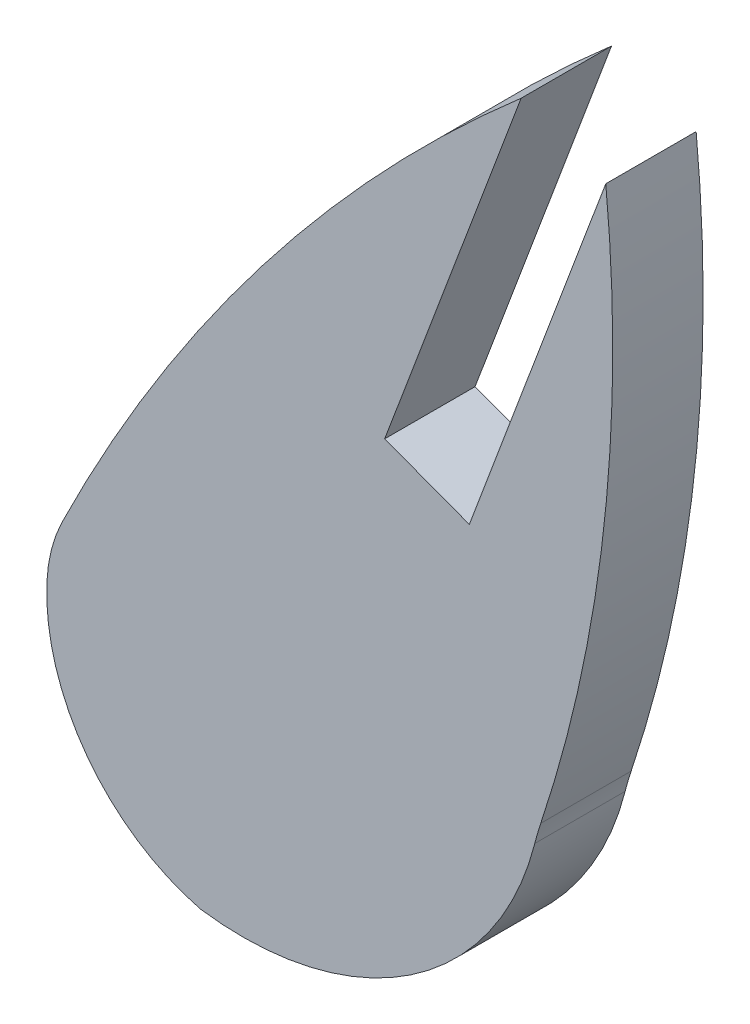
SolidWorks part; units mm, degrees
ref_plane "Front" through (0, 0, 0) normal (0, 0, 1) x (1, 0, 0)
ref_plane "Top" through (0, 0, 0) normal (0, 1, 0) x (1, 0, 0)
ref_plane "Right" through (0, 0, 0) normal (1, 0, 0) x (0, 0, -1)
sketch "Sketch1" plane through (0, 0, 0) normal (0, 0, 1) x (1, 0, 0)
  line L0 (-834.8343, -87.679) -> (-839.3645, -99.7367)
  line L1 (-839.3645, -99.7367) -> (-842.1728, -98.6816)
  line L2 (-842.1728, -98.6816) -> (-837.6427, -86.6239)
  arc A0 (-848.2815, -115.2586) -> (-837.1909, -107.8226) centre (-846.8822, -105.357) ccw
  arc A1 (-836.992, -107.1425) -> (-834.8343, -87.679) centre (-881.661, -92.3393) ccw
  arc A2 (-848.2815, -115.2586) -> (-853.3861, -108.4206) centre (-846.6302, -108.7016) cw
  arc A3 (-852.8802, -106.4281) -> (-837.6427, -86.6239) centre (-796.449, -134.0827) cw
  arc A4 (-853.3861, -108.4206) -> (-852.8802, -106.4281) centre (-848.3904, -108.6284) cw
  arc A5 (-836.992, -107.1425) -> (-837.1909, -107.8226) centre (-827.4997, -110.2882) ccw
  dimension "D1" = 3
  dimension "D5" = 5
  dimension "D6" = 10
  dimension "D2" = 3
  dimension "D3" = 90
  dimension "D4" = 90
extrude "Base-Extrude" add sketch "Sketch1" along normal blind 3
